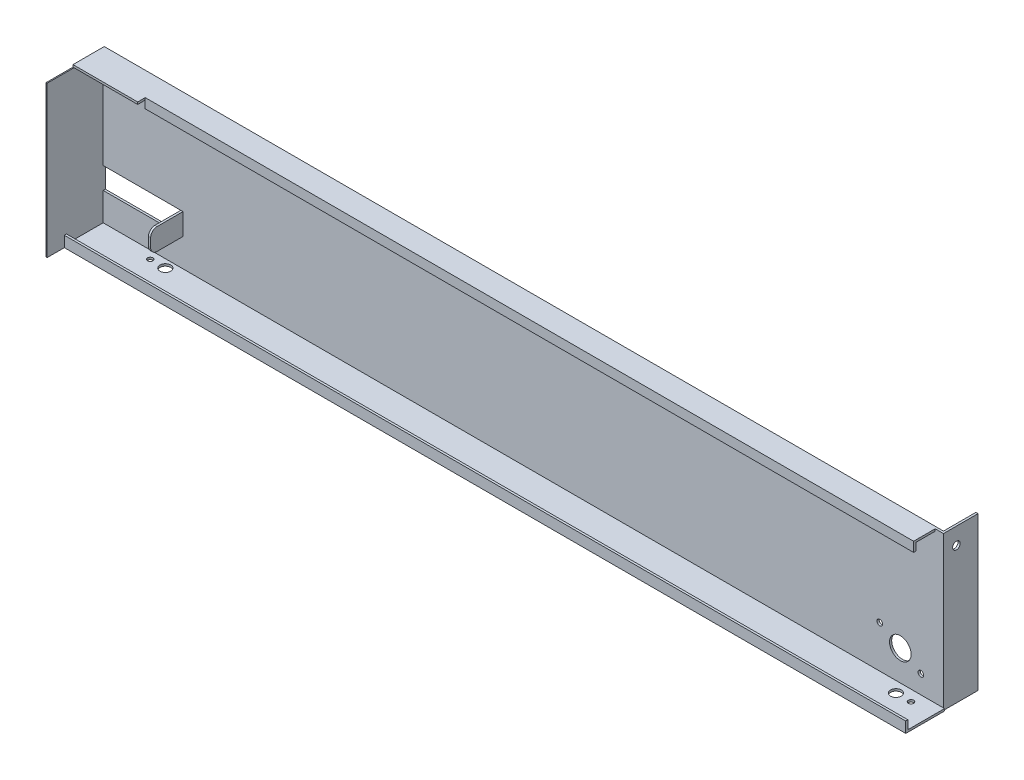
SolidWorks part; units mm, degrees
ref_plane "Alzado" through (0, 0, 0) normal (0, 0, 1) x (1, 0, 0)
ref_plane "Planta" through (0, 0, 0) normal (0, 1, 0) x (1, 0, 0)
ref_plane "Vista lateral" through (0, 0, 0) normal (1, 0, 0) x (0, 0, -1)
sketch "Croquis1" plane through (0, 0, 0) normal (0, 0, 1) x (1, 0, 0)
  line L1 (-195, -35.5) -> (195, -35.5)
  line L2 (-195, -35.5) -> (-195, 35.5)
  line L3 (-195, 35.5) -> (195, 35.5)
  line L4 (195, -35.5) -> (195, 35.5)
  line L5 (-195, -35.5) -> (195, 35.5) construction
  line L6 (-195, 35.5) -> (195, -35.5) construction
  point P0 (0, 0)
  dimension "D1" = 71
  dimension "D2" = 390
extrude "Saliente-Extruir1" add sketch "Croquis1" along normal blind 1
sketch "Croquis3" plane through (0, 0, 1) normal (0, 0, 1) x (1, 0, 0)
  line L0 (-195, 35.5) -> (-165, 35.5) construction
  line L1 (195, 35.5) -> (-195, 35.5) construction
  line L3 (-165, 35.5) -> (191.15, 35.5)
  line L4 (-165, 35.5) -> (-165, 34.5)
  line L5 (-165, 34.5) -> (191.15, 34.5)
  line L6 (191.15, 35.5) -> (191.15, 34.5)
  dimension "D1" = 30
  dimension "D2" = 1
  dimension "D3" = 356.15
extrude "Saliente-Extruir3" add sketch "Croquis3" along normal blind 10
sketch "Croquis4" plane through (0, 34.5, 0) normal (0, -1, 0) x (1, 0, 0)
  line L1 (-165, 11) -> (191.15, 11)
  line L2 (-165, 11) -> (-165, 10)
  line L3 (-165, 10) -> (191.15, 10)
  line L4 (191.15, 11) -> (191.15, 10)
  dimension "D1" = 1
  dimension "D2" = 356.15
extrude "Saliente-Extruir4" add sketch "Croquis4" along normal blind 3.5
sketch "Croquis5" plane through (0, 0, 1) normal (0, 0, 1) x (1, 0, 0)
  line L1 (-195, 35.5) -> (-165, 35.5)
  line L2 (-195, 35.5) -> (-195, 34.5)
  line L3 (-195, 34.5) -> (-165, 34.5)
  line L4 (-165, 35.5) -> (-165, 34.5)
extrude "Saliente-Extruir5" add sketch "Croquis5" along normal blind 13.5
sketch "Croquis6" plane through (0, 0, 1) normal (0, 0, 1) x (1, 0, 0)
  line L1 (-195, 34.5) -> (-194.5, 34.5)
  line L2 (-195, 34.5) -> (-195, -35.5)
  line L3 (-195, -35.5) -> (-194.5, -35.5)
  line L4 (-194.5, 34.5) -> (-194.5, -35.5)
  dimension "D1" = 70
  dimension "D2" = 0.5
extrude "Saliente-Extruir6" add sketch "Croquis6" along normal blind 26
sketch "Croquis7" plane through (0, 0, 1) normal (0, 0, 1) x (1, 0, 0)
  line L1 (-194.5, -35.5) -> (195.5, -35.5)
  line L2 (-194.5, -35.5) -> (-194.5, -34.5)
  line L3 (-194.5, -34.5) -> (195.5, -34.5)
  line L4 (195.5, -35.5) -> (195.5, -34.5)
  dimension "D1" = 1
extrude "Saliente-Extruir7" add sketch "Croquis7" along normal blind 18
sketch "Croquis8" plane through (0, -34.5, 0) normal (0, 1, 0) x (1, 0, 0)
  line L1 (-194.5, -19) -> (195.5, -19)
  line L2 (-194.5, -19) -> (-194.5, -18)
  line L3 (-194.5, -18) -> (195.5, -18)
  line L4 (195.5, -19) -> (195.5, -18)
  dimension "D1" = 1
  dimension "D2" = 390
extrude "Saliente-Extruir8" add sketch "Croquis8" along normal blind 4
sketch "Croquis11" plane through (0, 0, 1) normal (0, 0, 1) x (1, 0, 0)
  line L0 (-194.5, -34.5) -> (-158.5, -34.5) construction
  line L1 (195, -34.5) -> (-194.5, -34.5) construction
  line L2 (-158.5, -34.5) -> (-158.5, -21.5) construction
  line L4 (-158.5, -21.5) -> (-194.5, -21.5)
  line L5 (-158.5, -21.5) -> (-158.5, -11.5)
  line L6 (-158.5, -11.5) -> (-194.5, -11.5)
  line L7 (-194.5, -21.5) -> (-194.5, -11.5)
  dimension "D1" = 36
  dimension "D2" = 13
  dimension "D3" = 10
extrude "Cortar-Extruir1" cut sketch "Croquis11" against normal up to next
sketch "Croquis12" plane through (0, 0, 1) normal (0, 0, 1) x (1, 0, 0)
  line L1 (-158.5, -11.5) -> (-157.5, -11.5)
  line L2 (-158.5, -11.5) -> (-158.5, -21.5)
  line L3 (-158.5, -21.5) -> (-157.5, -21.5)
  line L4 (-157.5, -11.5) -> (-157.5, -21.5)
  dimension "D1" = 10
  dimension "D2" = 1
extrude "Saliente-Extruir11" add sketch "Croquis12" along normal blind 15
fillet "Redondeo1" radius 3 2 edges at (-158, -21.5, 16) (-158, -11.5, 16)
sketch "Croquis13" plane through (-158.5, 0, 0) normal (-1, 0, 0) x (0, 0, 1)
  line L0 (0, -16.5) -> (8.5, -16.5) construction
  line L1 (0, -21.5) -> (0, -11.5) construction
  line L2 (8.5, -16.5) -> (10.5, -16.5) construction
  circle A0 centre (10.5, -16.5) radius 2
  dimension "D3" = 4
  dimension "D1" = 8.5
  dimension "D2" = 2
extrude "Saliente-Extruir12" add sketch "Croquis13" along normal blind 1
sketch "Croquis14" plane through (-195, 0, 0) normal (-1, 0, 0) x (0, 0, 1)
  line L0 (14.5, 34.5) -> (0, 34.5) construction
  line L1 (0, 35.5) -> (0, -35.5) construction
  line L2 (0, 34.5) -> (5.81, 34.5) construction
  line L3 (5.81, 34.5) -> (5.81, 30.25) construction
  circle A0 centre (5.81, 30.25) radius 1.75
  dimension "D2" = 4.25
  dimension "D3" = 3.5
  dimension "D1" = 5.81
extrude "Cortar-Extruir2" cut sketch "Croquis14" against normal up to next
sketch "Croquis16" plane through (0, 0, 1) normal (0, 0, 1) x (1, 0, 0)
  line L0 (195, -34.5) -> (195, -26) construction
  line L1 (195, -34.5) -> (195, 35.5) construction
  line L3 (195, -34.5) -> (195, -17.1) construction
  line L6 (195, -34.5) -> (195, -20.5) construction
  line L7 (195, -20.5) -> (175, -20.5) construction
  line L9 (165.4737, -15) -> (184.5263, -26)
  circle A2 centre (175, -20.5) radius 5
  circle A3 centre (184.5263, -26) radius 1.3
  circle A4 centre (165.4737, -15) radius 1.3
  point P17 (175, -20.5)
  dimension "D3" = 2.6
  dimension "D7" = 2.6
  dimension "D10" = 10
  dimension "D9" = 20
  dimension "D12" = 11
extrude "Cortar-Extruir4" cut sketch "Croquis16" against normal blind 1 contours A4 | A2 | A3
sketch "Croquis25" plane through (0, -35.5, 0) normal (0, -1, 0) x (1, 0, 0)
  line L0 (195, 0) -> (195, 6.05) construction
  line L2 (195, 6.05) -> (185, 6.05) construction
  line L3 (185, 6.05) -> (178, 6.05) construction
  line L5 (-195, 0) -> (-195, 4.78) construction
  line L6 (-195, 27) -> (-195, 0) construction
  line L7 (-195, 4.78) -> (-168.9, 4.78) construction
  line L9 (-168.9, 4.78) -> (-161.9, 4.78) construction
  circle A2 centre (-168.9, 4.78) radius 1.25
  circle A3 centre (-161.9, 4.78) radius 2.5
  circle A4 centre (185, 6.05) radius 1.25
  circle A5 centre (178, 6.05) radius 2.5
  dimension "D3" = 2.5
  dimension "D5" = 5
  dimension "D6" = 26.1
  dimension "D7" = 2.5
  dimension "D9" = 5
  dimension "D1" = 6.05
  dimension "D2" = 10
  dimension "D4" = 7
  dimension "D8" = 7
extrude "Cortar-Extruir5" cut sketch "Croquis25" against normal blind 1
sketch "Croquis30" plane through (0, 0, 0) normal (0, 0, -1) x (-1, 0, 0)
  line L1 (-195, 35.5) -> (-194, 35.5)
  line L2 (-195, 35.5) -> (-195, -35.5)
  line L3 (-195, -35.5) -> (-194, -35.5)
  line L4 (-194, 35.5) -> (-194, -35.5)
  line L5 (195, -35.5) -> (-195, -35.5) construction
  dimension "D1" = 71
  dimension "D2" = 1
extrude "Saliente-Extruir15" add sketch "Croquis30" along normal blind 15
sketch "Croquis31" plane through (195, 0, 0) normal (1, 0, 0) x (0, 0, -1)
  line L0 (-1, 35.5) -> (-1, 27.7) construction
  line L1 (-1, -34.5) -> (-1, 35.5) construction
  line L2 (-1, 27.7) -> (5, 27.7) construction
  circle A0 centre (5, 27.7) radius 1.75
  dimension "D3" = 3.5
  dimension "D1" = 7.8
  dimension "D2" = 6
extrude "Cortar-Extruir12" cut sketch "Croquis31" against normal blind 1 contours A0
